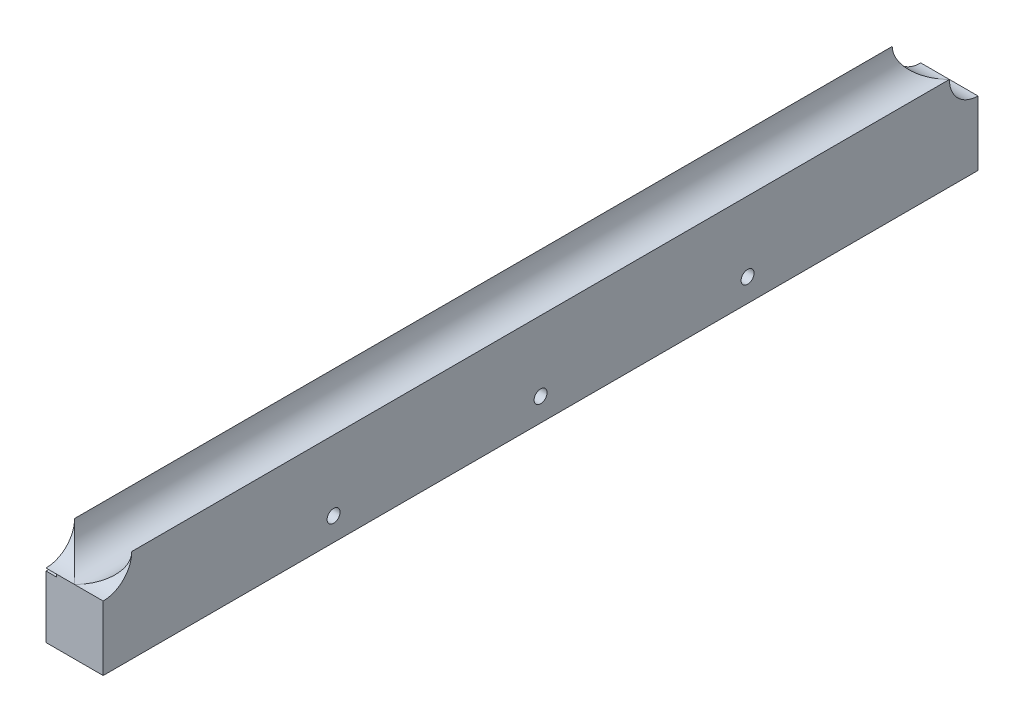
SolidWorks part; units mm, degrees
material "ABS"
ref_plane "Front Plane" through (0, 0, 0) normal (0, 0, 1) x (1, 0, 0)
ref_plane "Top Plane" through (0, 0, 0) normal (0, 1, 0) x (1, 0, 0)
ref_plane "Right Plane" through (0, 0, 0) normal (1, 0, 0) x (0, 0, -1)
sketch "Sketch1" plane through (0, 0, 0) normal (0, 1, 0) x (1, 0, 0)
  line L1 (-11.05, 169.05) -> (11.05, 169.05)
  line L2 (-11.05, 169.05) -> (-11.05, -169.05)
  line L3 (-11.05, -169.05) -> (11.05, -169.05)
  line L4 (11.05, 169.05) -> (11.05, -169.05)
  line L5 (-11.05, 169.05) -> (11.05, -169.05) construction
  line L6 (-11.05, -169.05) -> (11.05, 169.05) construction
  point P0 (0, 0)
  dimension "D1" = 338.1
  dimension "D2" = 22.1
extrude "Boss-Extrude1" add sketch "Sketch1" along normal blind 36
sketch "Sketch2" plane through (0, 0, 169.05) normal (0, 0, 1) x (1, 0, 0)
  line L0 (11.05, 36) -> (11.05, 0) construction
  circle A0 centre (0, 36) radius 11.05
  dimension "D1" = 22.1
extrude "Cut-Extrude1" cut sketch "Sketch2" against normal up to next
sketch "Sketch3" plane through (11.05, 0, 0) normal (1, 0, 0) x (0, 0, -1)
  circle A0 centre (-169.05, 36) radius 11.05
  circle A1 centre (169.05, 36) radius 11.05
  dimension "D1" = 22.1
  dimension "D2" = 22.1
extrude "Cut-Extrude2" cut sketch "Sketch3" against normal through all
sketch "Sketch4" plane through (-11.05, 0, 0) normal (1, 0, 0) x (0, 0, -1)
  line L0 (0, 36) -> (0, 0) construction
  line L1 (-158, 36) -> (158, 36) construction
  point P9 (80, 8.94)
  point P10 (-80, 8.94)
  point P19 (0, 8.94)
  dimension "D1" = 80
  dimension "D2" = 16.01
hole_wizard "Ø5.0mm Dowel Hole4" positions "Sketch17" profile "Sketch18" hole size "Ø5.0" standard "ANSI Metric" end condition through all
sketch "Sketch17" plane through (11.05, 0, 0) normal (1, 0, 0) x (0, 0, -1)
  point P0 (-80, 8.94)
  point P3 (0, 8.94)
  point P6 (80, 8.94)
sketch "Sketch18" plane through (11.05, 8.94, 80) normal (0, 1, 0) x (0, 0, -1)
  line L0 (0, 0) -> (0, 22.1)
  line L1 (0, 22.1) -> (2.5, 22.1)
  line L2 (2.5, 22.1) -> (2.5, 0)
  line L5 (2.5, 0) -> (0, 0)
  line L11 (0, -6.35) -> (0, 107.95) construction
  dimension "Thru Hole Dia." = 5
  dimension "Thru Hole Depth" = 22.1
sketch "Sketch16" plane through (0, 0, -169.05) normal (0, 0, -1) x (-1, 0, 0)
  line L1 (11.05, 24.95) -> (7.05, 24.95)
  line L2 (11.05, 24.95) -> (11.05, 23.95)
  line L3 (11.05, 23.95) -> (7.05, 23.95)
  line L4 (7.05, 24.95) -> (7.05, 23.95)
  dimension "D1" = 1
  dimension "D2" = 4
extrude "Cut-Extrude3" cut sketch "Sketch16" against normal through all
sketch "Sketch19" plane through (0, 0, -169.05) normal (0, 0, -1) x (-1, 0, 0)
  line L0 (11.05, 0) -> (0, 11.975) construction
  line L1 (0, 11.975) -> (-11.05, 23.95) construction
  line L2 (-11.05, 24.95) -> (-11.05, 0) construction
  circle A0 centre (-5.525, 17.9625) radius 2.5
  circle A1 centre (5.525, 5.9875) radius 2.5
  dimension "D1" = 5
extrude "Cut-Extrude4" cut sketch "Sketch19" against normal blind 10
